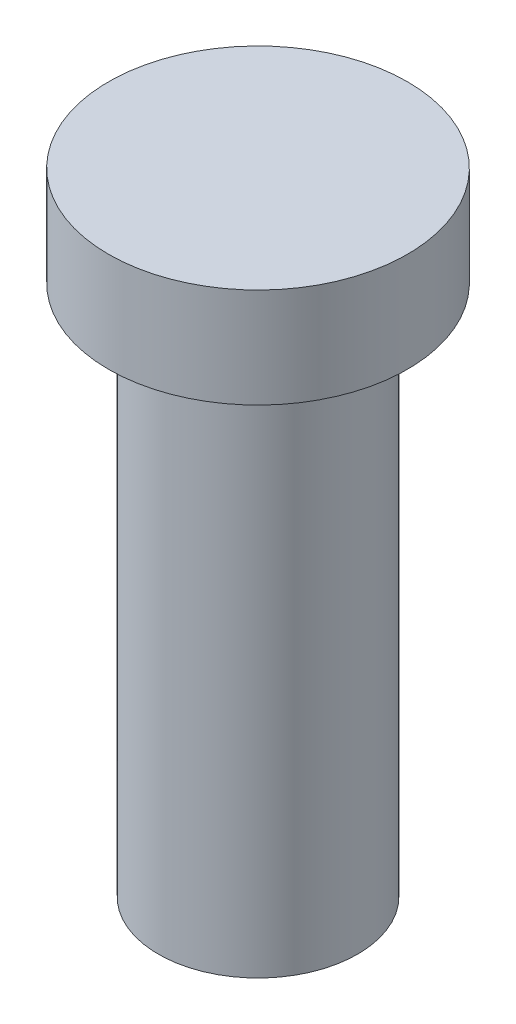
SolidWorks part; units mm, degrees
material "尼龙 101"
ref_plane "前视基准面" through (0, 0, 0) normal (0, 0, 1) x (1, 0, 0)
ref_plane "上视基准面" through (0, 0, 0) normal (0, 1, 0) x (1, 0, 0)
ref_plane "右视基准面" through (0, 0, 0) normal (1, 0, 0) x (0, 0, -1)
other "Configuration Table"
sketch "草图1" plane through (0, 0, 0) normal (0, 1, 0) x (1, 0, 0)
  circle A0 centre (0, 0) radius 2.25
extrude "凸台-拉伸1" add sketch "草图1" along normal blind 1.5
sketch "草图2" plane through (0, 0, 0) normal (0, -1, 0) x (1, 0, 0)
  circle A0 centre (0, 0) radius 1.5
extrude "凸台-拉伸2" add sketch "草图2" along normal blind 8
